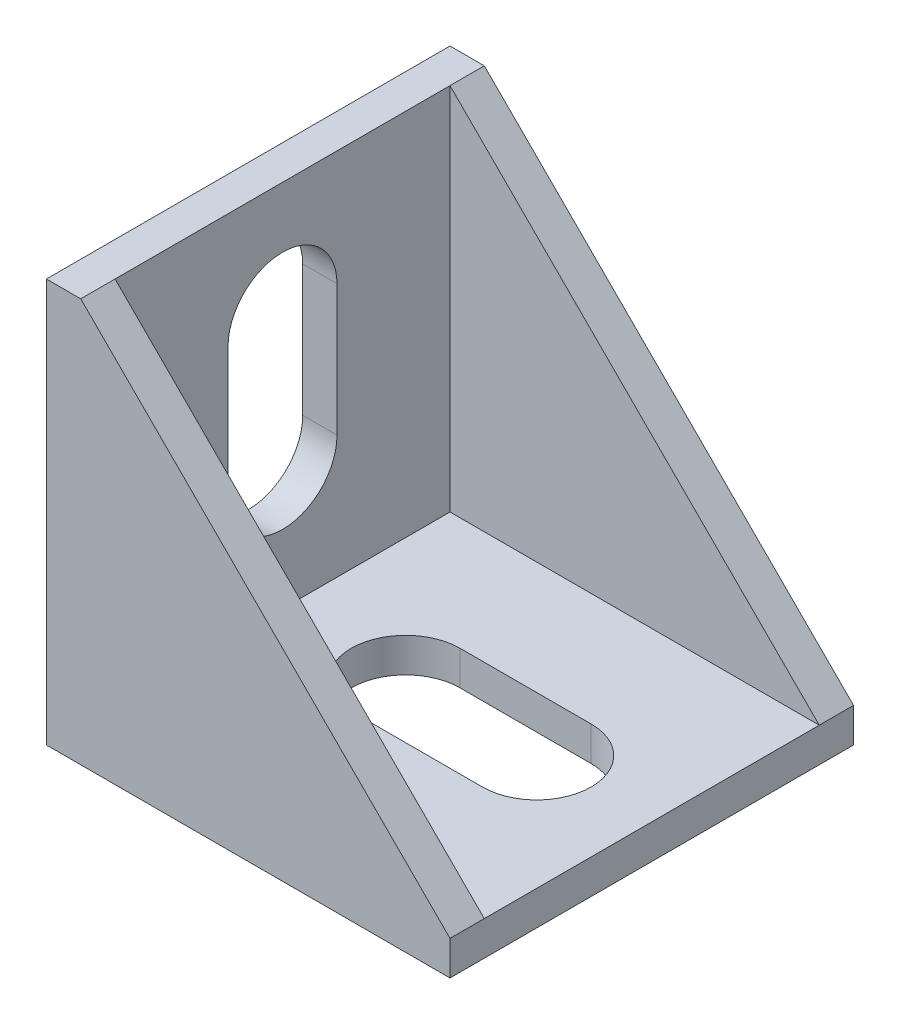
SolidWorks part; units mm, degrees
ref_plane "Přední rovina" through (0, 0, 0) normal (0, 0, 1) x (1, 0, 0)
ref_plane "Horní rovina" through (0, 0, 0) normal (0, 1, 0) x (1, 0, 0)
ref_plane "Pravá rovina" through (0, 0, 0) normal (1, 0, 0) x (0, 0, -1)
sketch "Skica1" plane through (0, 0, 0) normal (0, 1, 0) x (1, 0, 0)
  line L0 (-2.2, 0) -> (4.3, 0) construction
  line L1 (-10, -10) -> (10, -10)
  line L2 (-10, -10) -> (-10, 10)
  line L3 (-10, 10) -> (10, 10)
  line L4 (10, -10) -> (10, 10)
  line L5 (-10, -10) -> (10, 10) construction
  line L6 (-10, 10) -> (10, -10) construction
  line L7 (-2.2, 2.7) -> (4.3, 2.7)
  line L8 (-2.2, -2.7) -> (4.3, -2.7)
  arc A0 (-2.2, 2.7) -> (-2.2, -2.7) centre (-2.2, 0) ccw
  arc A1 (4.3, -2.7) -> (4.3, 2.7) centre (4.3, 0) ccw
  point P0 (0, 0)
  point P8 (1.05, 0)
  dimension "D1" = 20
  dimension "D2" = 20
  dimension "D3" = 6.5
  dimension "D4" = 5.4
  dimension "D5" = 5.7
extrude "Přidat vysunutím1" add sketch "Skica1" along normal blind 1.7
sketch "Skica2" plane through (0, 1.7, 0) normal (0, 1, 0) x (1, 0, 0)
  line L0 (-10, -10) -> (10, -10) construction
  line L1 (-10, 10) -> (-8.3, 10)
  line L2 (-10, 10) -> (-10, -10)
  line L3 (-10, -10) -> (-8.3, -10)
  line L4 (-8.3, 10) -> (-8.3, -10)
  line L5 (-10, 10) -> (-8.3, -10) construction
  line L6 (-10, -10) -> (-8.3, 10) construction
  point P4 (-9.15, 0)
  dimension "D1" = 1.7
extrude "Přidat vysunutím2" add sketch "Skica2" along normal blind 18.3
sketch "Skica3" plane through (-8.3, 0, 0) normal (1, 0, 0) x (0, 0, -1)
  line L0 (0, 14.3) -> (0, 7.8) construction
  line L1 (2.7, 14.3) -> (2.7, 7.8)
  line L2 (-2.7, 14.3) -> (-2.7, 7.8)
  line L3 (-10, 20) -> (10, 20) construction
  arc A0 (2.7, 14.3) -> (-2.7, 14.3) centre (0, 14.3) ccw
  arc A1 (-2.7, 7.8) -> (2.7, 7.8) centre (0, 7.8) ccw
  point P3 (0, 11.05)
  point P10 (0, 20)
  dimension "D1" = 5.7
  dimension "D2" = 6.5
  dimension "D3" = 5.4
extrude "Odebrat vysunutím1" cut sketch "Skica3" against normal up to surface (1.7 mm away) up to face at (-10, 10, 0)
sketch "Skica4" plane through (-8.3, 0, 0) normal (1, 0, 0) x (0, 0, -1)
  line L0 (-10, 1.7) -> (10, 1.7) construction
  line L1 (-10, 20) -> (-8.3, 20)
  line L2 (-10, 20) -> (-10, 1.7)
  line L3 (-10, 1.7) -> (-8.3, 1.7)
  line L4 (-8.3, 20) -> (-8.3, 1.7)
  line L5 (-10, 20) -> (-8.3, 1.7) construction
  line L6 (-10, 1.7) -> (-8.3, 20) construction
  line L7 (0, 20) -> (0, 1.7) construction
  line L8 (-10, 20) -> (10, 20) construction
  line L9 (10, 1.7) -> (8.3, 1.7)
  line L10 (10, 20) -> (10, 1.7)
  line L11 (10, 20) -> (8.3, 20)
  line L12 (8.3, 20) -> (8.3, 1.7)
  point P4 (-9.15, 10.85)
  dimension "D1" = 1.7
extrude "Přidat vysunutím3" add sketch "Skica4" along normal blind 18.3
chamfer "Zkosení1" distance 18.3 angle 45 2 edges at (10, 20, -9.15) (10, 20, 9.15)
